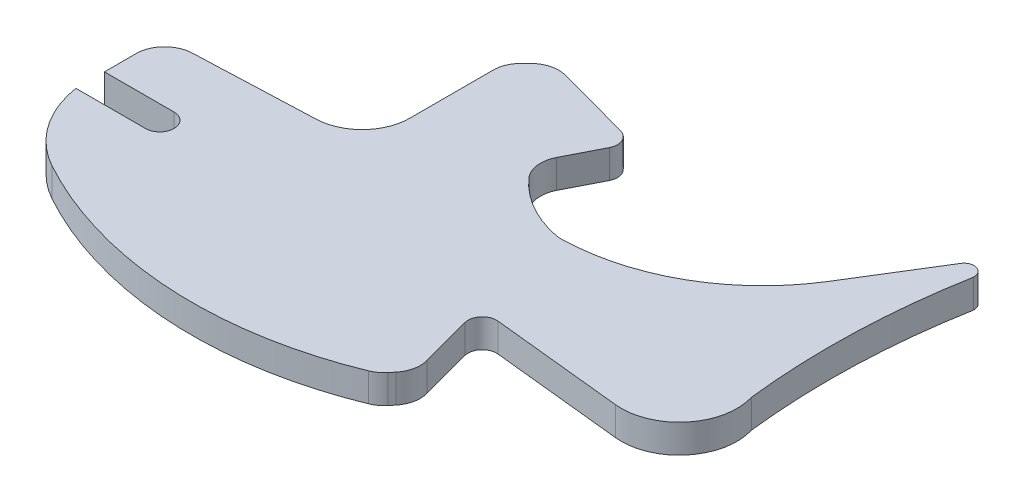
SolidWorks part; units mm, degrees
ref_plane "Front Plane" through (0, 0, 0) normal (0, 0, 1) x (1, 0, 0)
ref_plane "Top Plane" through (0, 0, 0) normal (0, 1, 0) x (1, 0, 0)
ref_plane "Right Plane" through (0, 0, 0) normal (1, 0, 0) x (0, 0, -1)
sketch "Sketch1" plane through (0, 0, 0) normal (0, 1, 0) x (1, 0, 0)
  line L0 (0, 0) -> (7.31, 0)
  line L1 (7.31, -3) -> (0, -3)
  line L2 (57.1266, 19.0285) -> (62.3904, 27.549)
  line L3 (30.69, 14.31) -> (34.24, 21.27)
  line L4 (34.24, 21.27) -> (22.85, 24.35)
  line L5 (22.85, 24.35) -> (20.25, 21.8189)
  line L6 (20.25, 21.8189) -> (20.25, 7.0033)
  line L7 (0, 0) -> (0, 6.2048)
  line L8 (0, 6.2048) -> (20.25, 7.0033)
  line L9 (41.17, -1.78) -> (57.1266, -3.44)
  line L10 (43.59, -10.8) -> (41.17, -1.78)
  arc A0 (7.31, 0) -> (7.31, -3) centre (7.31, -1.5) cw
  arc A1 (0, -3) -> (5.8235, -11.3202) centre (11.3443, -1.258) ccw
  arc A2 (41.7681, -13.034) -> (43.59, -10.8) centre (-32.6907, 49.5473) ccw
  arc A3 (41.7681, -13.034) -> (5.8235, -11.3202) centre (25.5511, 24.6355) cw
  arc A4 (63.57, 4.39) -> (64.3157, 26.9808) centre (140.5807, 13.1557) cw
  arc A5 (64.3157, 26.9808) -> (62.3904, 27.549) centre (63.2755, 27.0022) ccw
  arc A6 (57.1266, 19.0285) -> (38.89, 8.78) centre (38.748, 30.3825) cw
  arc A7 (38.89, 8.78) -> (30.69, 14.31) centre (40.9177, 20.6314) cw
  arc A8 (57.1266, -3.44) -> (63.57, 4.39) centre (57.7559, 2.6084) ccw
  point P4 (41.17, -1.78)
  point P9 (8.81, -1.5)
  point P11 (30.69, 14.31)
  point P14 (63.57, 28)
  point P15 (38.89, 8.78)
  point P21 (23.5978, -16.33)
  point P24 (63.57, 4.39)
  point P29 (22.85, 24.35)
  point P30 (63.57, 28)
  point P31 (20.25, 21.8189)
  point P32 (0, 0)
  point P34 (34.24, 21.27)
  point P42 (0, 0)
  point P43 (20.25, 21.8189)
  point P44 (0, 0)
  dimension "D1" = 1.5
  dimension "D21" = 77.508
  dimension "D22" = 11.4773
  dimension "D23" = 97.2653
  dimension "D24" = 41.0121
  dimension "D25" = 1.0404
  dimension "D26" = 21.6029
  dimension "D27" = 12.0236
  dimension "D28" = 6.081
  dimension "D2" = 8.81
  dimension "D3" = 43.59
  dimension "D4" = 10.8
  dimension "D5" = 16.33
  dimension "D6" = 63.57
  dimension "D7" = 41.17
  dimension "D8" = 1.78
  dimension "D9" = 4.39
  dimension "D10" = 28
  dimension "D11" = 8.78
  dimension "D12" = 38.89
  dimension "D13" = 30.69
  dimension "D14" = 14.31
  dimension "D15" = 34.24
  dimension "D16" = 21.27
  dimension "D17" = 22.85
  dimension "D18" = 24.35
  dimension "D19" = 20.25
  dimension "D20" = 1.66
  dimension "D29" = 5.8235
  dimension "D30" = 11.3443
  dimension "D31" = 38.748
  dimension "D32" = 6.2048
  dimension "D33" = 7.0033
  dimension "D34" = 21.8189
extrude "Boss-Extrude1" add sketch "Sketch1" along normal blind 3 contours L6 L8 L7 L0 A0 L1 A1 A3 A2 L10 L9 A8 A4 A5 L2 A6 A7 L3 L4 L5
fillet "Fillet1" radius 1.5 1 edges at (41.17, 1.5, 1.78)
fillet "Fillet2" radius 3 7 edges at (38.89, 1.5, -8.78) (41.7681, 1.5, 13.034) (43.59, 1.5, 10.8) (0, 1.5, -6.2048) (20.25, 1.5, -21.8189) (22.85, 1.5, -24.35) (30.69, 1.5, -14.31)
fillet "Fillet3" radius 1.5 1 edges at (34.24, 1.5, -21.27)
fillet "Fillet4" radius 5 1 edges at (20.25, 1.5, -7.0033)
